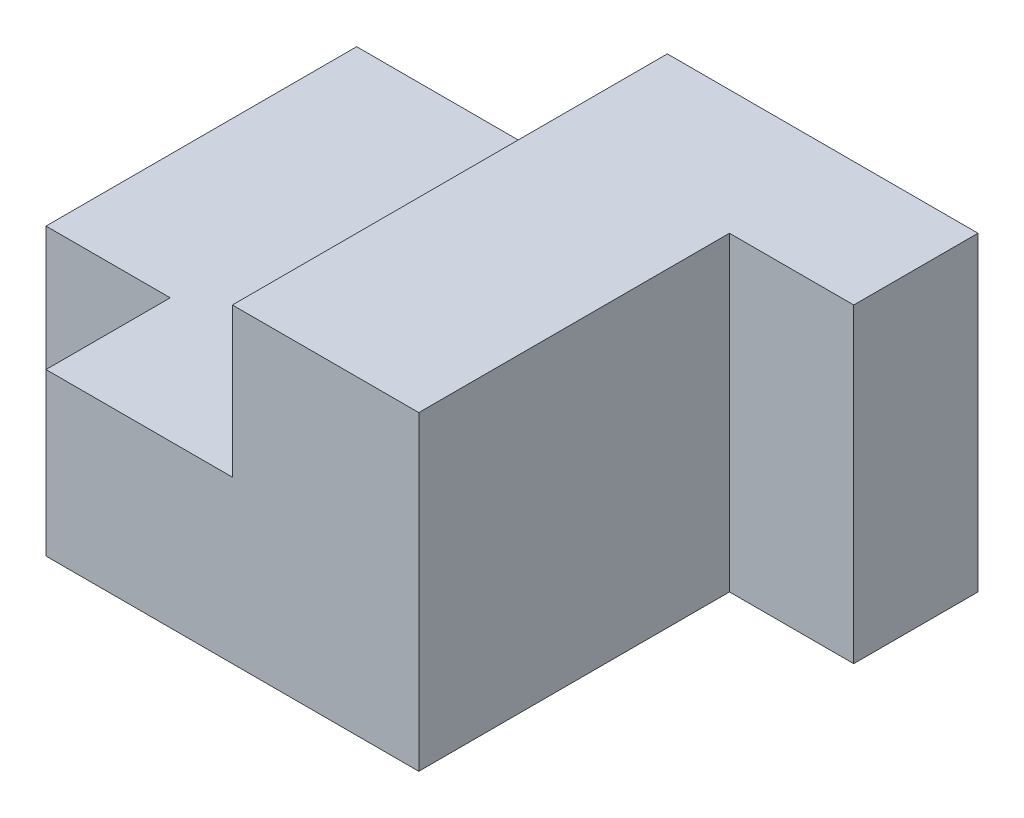
SolidWorks part; units mm, degrees
ref_plane "Front Plane" through (0, 0, 0) normal (0, 0, 1) x (1, 0, 0)
ref_plane "Top Plane" through (0, 0, 0) normal (0, 1, 0) x (1, 0, 0)
ref_plane "Right Plane" through (0, 0, 0) normal (1, 0, 0) x (0, 0, -1)
sketch "Sketch1" plane through (0, 0, 0) normal (0, 0, 1) x (1, 0, 0)
  line L0 (-33.027, 100.8311) -> (-83.027, 100.8311)
  line L1 (-83.027, 100.8311) -> (-83.027, 76.8311)
  line L2 (-83.027, 76.8311) -> (-133.027, 76.8311)
  line L3 (-133.027, 76.8311) -> (-133.027, 50.8311)
  line L4 (-133.027, 50.8311) -> (-33.027, 50.8311)
  line L5 (-33.027, 50.8311) -> (-33.027, 100.8311)
  dimension "D1" = 50
  dimension "D2" = 100
  dimension "D3" = 26
  dimension "D4" = 50
extrude "Boss-Extrude1" add sketch "Sketch1" along normal blind 70
sketch "Sketch2" plane through (0, 0, 70) normal (0, 0, 1) x (1, 0, 0)
  line L0 (-133.027, 50.8311) -> (-33.027, 50.8311) construction
  line L1 (-33.027, 100.8311) -> (-53.027, 100.8311)
  line L2 (-33.027, 100.8311) -> (-33.027, 50.8311)
  line L3 (-33.027, 50.8311) -> (-53.027, 50.8311)
  line L4 (-53.027, 100.8311) -> (-53.027, 50.8311)
  dimension "D1" = 20
extrude "Cut-Extrude1" cut sketch "Sketch2" against normal blind 50
sketch "Sketch3" plane through (0, 0, 70) normal (0, 0, 1) x (1, 0, 0)
  line L0 (-133.027, 50.8311) -> (-53.027, 50.8311) construction
  line L1 (-133.027, 76.8311) -> (-113.027, 76.8311)
  line L2 (-133.027, 76.8311) -> (-133.027, 50.8311)
  line L3 (-133.027, 50.8311) -> (-113.027, 50.8311)
  line L4 (-113.027, 76.8311) -> (-113.027, 50.8311)
  dimension "D1" = 20
extrude "Cut-Extrude2" cut sketch "Sketch3" against normal blind 20
